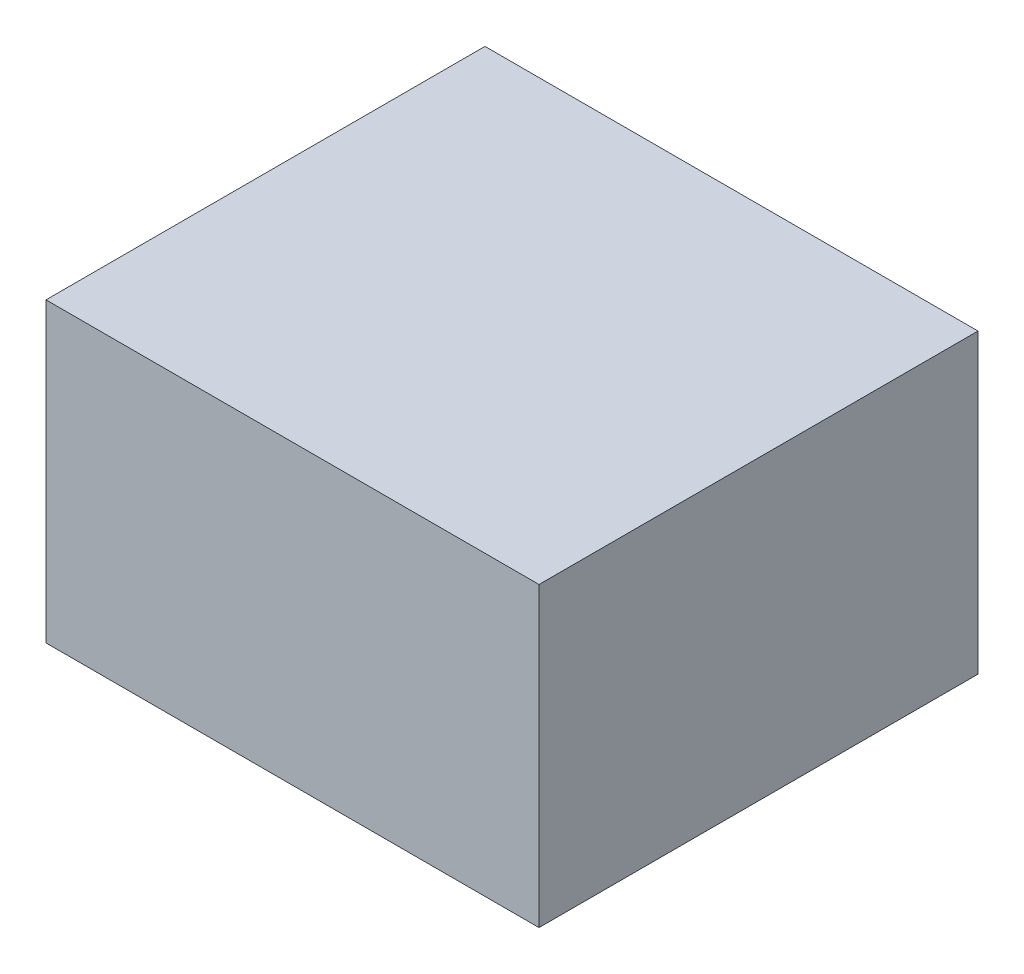
SolidWorks part; units mm, degrees
ref_plane "前视基准面" through (0, 0, 0) normal (0, 0, 1) x (1, 0, 0)
ref_plane "上视基准面" through (0, 0, 0) normal (0, 1, 0) x (1, 0, 0)
ref_plane "右视基准面" through (0, 0, 0) normal (1, 0, 0) x (0, 0, -1)
other "Configuration Table"
sketch "草图1" plane through (0, 0, 0) normal (0, 1, 0) x (1, 0, 0)
  line L1 (-36.5, 32.5) -> (36.5, 32.5)
  line L2 (-36.5, 32.5) -> (-36.5, -32.5)
  line L3 (-36.5, -32.5) -> (36.5, -32.5)
  line L4 (36.5, 32.5) -> (36.5, -32.5)
  line L5 (-36.5, 32.5) -> (36.5, -32.5) construction
  line L6 (-36.5, -32.5) -> (36.5, 32.5) construction
  point P0 (0, 0)
  dimension "D1" = 73
  dimension "D2" = 65
extrude "凸台-拉伸1" add sketch "草图1" along normal blind 44
